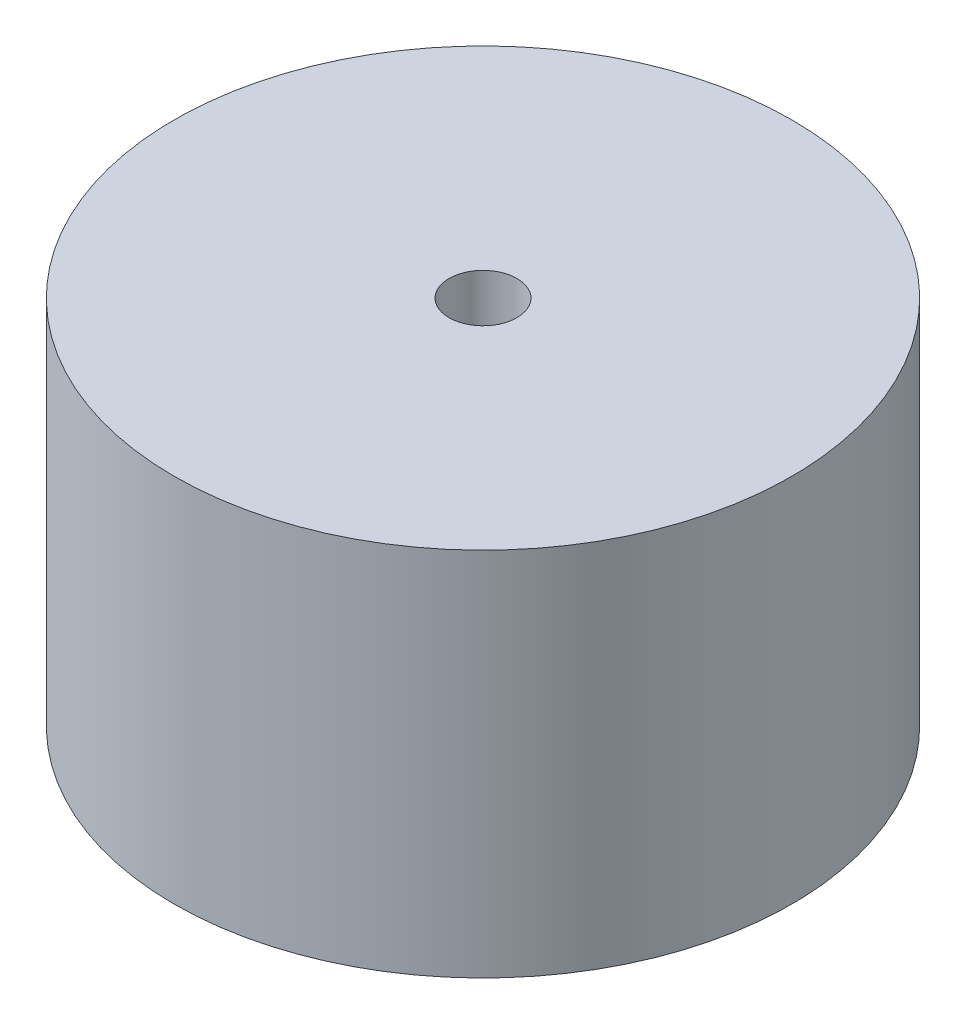
SolidWorks part; units mm, degrees
material "Liga 1060"
ref_plane "Plano frontal" through (0, 0, 0) normal (0, 0, 1) x (1, 0, 0)
ref_plane "Plano superior" through (0, 0, 0) normal (0, 1, 0) x (1, 0, 0)
ref_plane "Plano direito" through (0, 0, 0) normal (1, 0, 0) x (0, 0, -1)
sketch "Esboço1" plane through (0, 0, 0) normal (0, 1, 0) x (1, 0, 0)
  circle A0 centre (0, 0) radius 50
  circle A1 centre (0, 0) radius 5.5
  dimension "D1" = 100
  dimension "D2" = 11
extrude "Ressalto-extrusão1" add sketch "Esboço1" along normal blind 60
